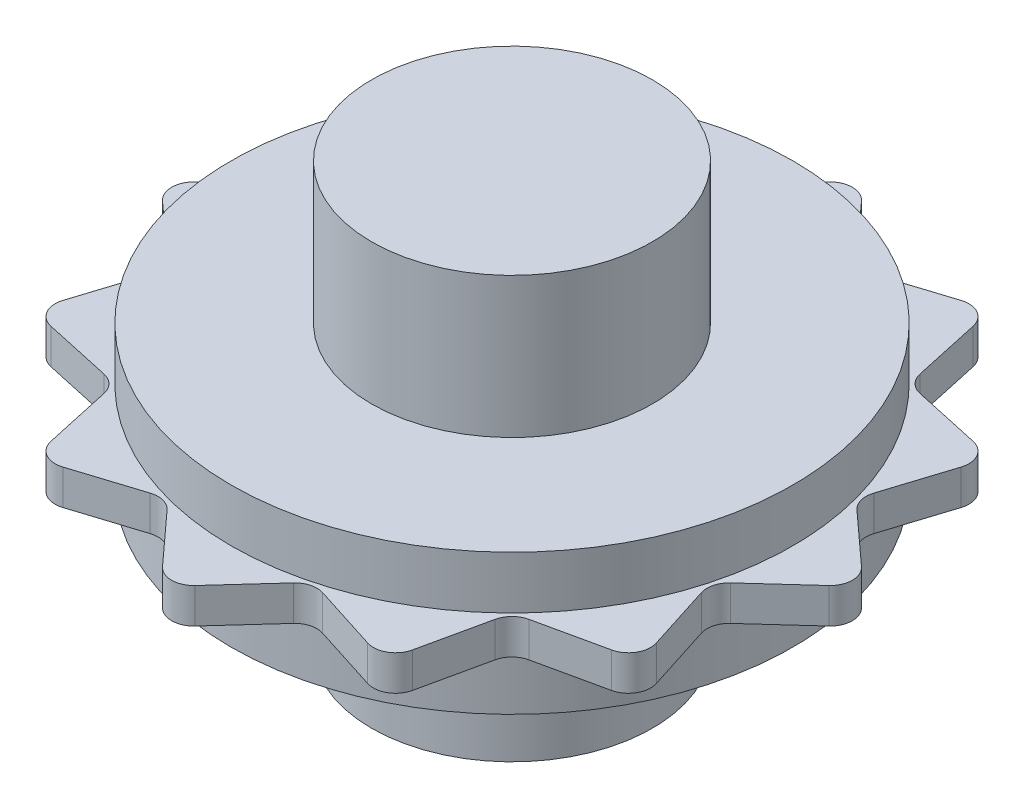
SolidWorks part; units mm, degrees
ref_plane "Front Plane" through (0, 0, 0) normal (0, 0, 1) x (1, 0, 0)
ref_plane "Top Plane" through (0, 0, 0) normal (0, 1, 0) x (1, 0, 0)
ref_plane "Right Plane" through (0, 0, 0) normal (1, 0, 0) x (0, 0, -1)
sketch "Sketch1" plane through (0, 0, 0) normal (0, 1, 0) x (1, 0, 0)
  circle A0 centre (0, 0) radius 6.35
  dimension "D1" = 12.7
extrude "Boss-Extrude1" add sketch "Sketch1" along normal blind 19.05
sketch "Sketch2" plane through (0, 0, 0) normal (0, 1, 0) x (1, 0, 0)
  circle A0 centre (0, 0) radius 12.7
  dimension "D1" = 25.4
extrude "Boss-Extrude2" add sketch "Sketch2" along normal blind 6.35 from offset 6.35
ref_plane "Plane1" through (0, 9.525, 0) normal (0, 1, 0) x (1, 0, 0)
sketch "Sketch3" plane through (0, 9.525, 0) normal (0, 1, 0) x (1, 0, 0)
  line L0 (0, 0) -> (0, -15.875) construction
  line L1 (0, 0) -> (-4.4774, -16.7099) construction
  line L2 (-3.287, -12.2673) -> (0, -15.875) construction
  line L3 (0, 0) -> (-9.078, -15.7235) construction
  line L4 (-3.287, -12.2673) -> (-7.9375, -13.7482) construction
  line L5 (-6.8917, -13.4151) -> (-3.8979, -12.4618)
  line L6 (-2.8552, -12.7412) -> (-0.7392, -15.0637)
  line L7 (-7.6951, -13.3283) -> (-6.35, -10.9985)
  line L8 (-6.35, -10.9985) -> (0, -12.7)
  line L9 (0, -12.7) -> (0, -15.3902)
  circle A0 centre (0, 0) radius 12.7 construction
  arc A1 (-0.7392, -15.0637) -> (0, -15.3902) centre (0, -14.3902) ccw
  circle A2 centre (0, 0) radius 15.875 construction
  arc A3 (-7.6951, -13.3283) -> (-6.8917, -13.4151) centre (-7.1951, -12.4623) ccw
  arc A4 (-3.8979, -12.4618) -> (-2.8552, -12.7412) centre (-3.5944, -13.4146) cw
  point P14 (-0.7392, -15.0637)
  dimension "D3" = 1
  dimension "D2" = 3.175
  dimension "D5" = 1
  dimension "D6" = 1
  dimension "D1" = 15
  dimension "D4" = 15
extrude "Boss-Extrude3" add sketch "Sketch3" along normal mid plane 1.5875
pattern_circular "CirPattern1" count 12 over 360 about axis through (0, 0, 0) along (0, 1, 0) of "Boss-Extrude3"
